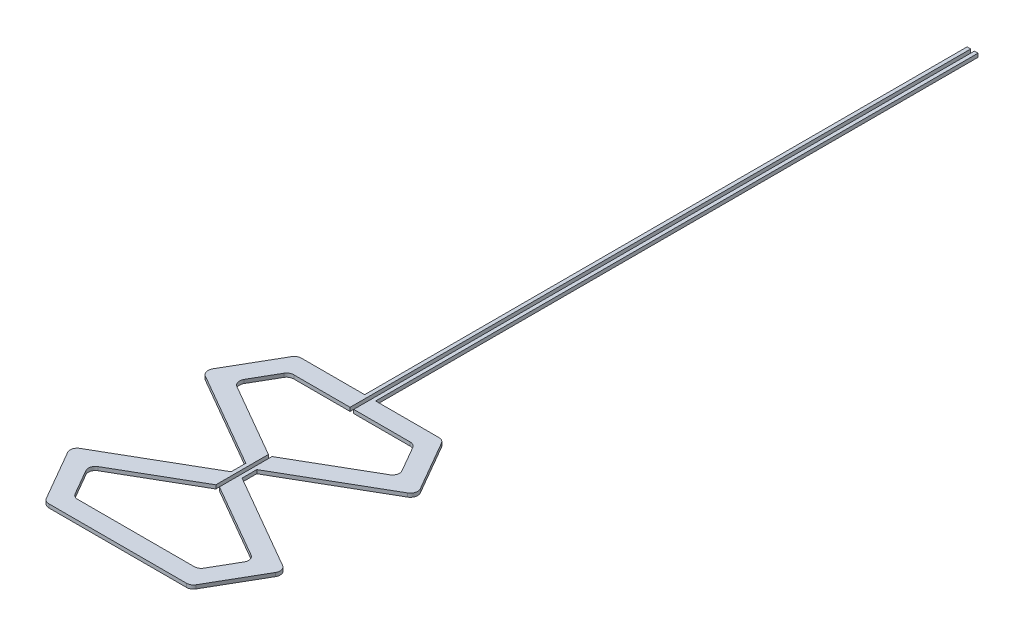
SolidWorks part; units mm, degrees
ref_plane "前视基准面" through (0, 0, 0) normal (0, 0, 1) x (1, 0, 0)
ref_plane "上视基准面" through (0, 0, 0) normal (0, 1, 0) x (1, 0, 0)
ref_plane "右视基准面" through (0, 0, 0) normal (1, 0, 0) x (0, 0, -1)
sketch "草图2" plane through (0, 0, 0) normal (0, 1, 0) x (1, 0, 0)
  line L0 (28.5, 19.9186) -> (20.5774, 33.641)
  line L1 (-28.551, -19.8303) -> (-20.5479, -33.692)
  line L2 (18.8453, 34.641) -> (-18.8453, 34.641)
  line L3 (-20.5774, 33.641) -> (-28.5, 19.9186)
  line L4 (15.9585, 29.641) -> (-15.9585, 29.641)
  line L5 (-18.9042, -34.641) -> (18.9042, -34.641)
  line L6 (20.5479, -33.692) -> (28.551, -19.8303)
  line L7 (-17.6906, 28.641) -> (-21.6699, 21.7487)
  line L8 (-27.7679, 17.1865) -> (0, 1.1547)
  line L9 (27.7679, 17.1865) -> (0, 1.1547)
  line L10 (-40, 0) -> (40, 0) construction
  line L11 (27.8562, -17.2375) -> (0, -1.1547)
  line L12 (-27.8562, -17.2375) -> (0, -1.1547)
  line L13 (-20.9378, 19.0167) -> (0, 6.9282)
  line L14 (21.0261, 19.0676) -> (0, 6.9282)
  line L15 (21.7208, 21.6604) -> (17.6906, 28.641)
  line L16 (-21.0261, -19.0676) -> (0, -6.9282)
  line L17 (30.5, 16.4545) -> (30, 17.3205) [skipped]
  line L18 (-30.5, -16.4545) -> (-30, -17.3205) [skipped]
  line L19 (21.0261, -19.0676) -> (0, -6.9282)
  line L20 (17.6612, -28.692) -> (21.7208, -21.6604)
  line L21 (-16.0174, -29.641) -> (16.0174, -29.641)
  line L22 (-21.7208, -21.6604) -> (-17.6612, -28.692)
  line L23 (-20, 34.641) -> (-29.5, 18.1865) construction
  line L24 (20, 34.641) -> (-20, 34.641) construction
  line L25 (-29.5, 18.1865) -> (0, 1.1547) construction
  line L26 (-17.1132, 29.641) -> (-22.6699, 20.0167) construction
  line L27 (-22.6699, 20.0167) -> (0, 6.9282) construction
  line L28 (17.1132, 29.641) -> (-17.1132, 29.641) construction
  line L29 (22.6699, 20.0167) -> (17.1132, 29.641) construction
  line L30 (29.5, 18.1865) -> (20, 34.641) construction
  line L31 (29.5, 18.1865) -> (0, 1.1547) construction
  line L32 (22.6699, 20.0167) -> (0, 6.9282) construction
  line L33 (-22.6699, -20.0167) -> (-17.1132, -29.641) construction
  line L34 (-22.6699, -20.0167) -> (0, -6.9282) construction
  line L35 (-29.5, -18.1865) -> (-20, -34.641) construction
  line L36 (-29.5, -18.1865) -> (0, -1.1547) construction
  line L37 (-17.1132, -29.641) -> (17.1132, -29.641) construction
  line L38 (-20, -34.641) -> (20, -34.641) construction
  line L39 (20, -34.641) -> (29.5, -18.1865) construction
  line L40 (17.1132, -29.641) -> (22.6699, -20.0167) construction
  line L41 (22.6699, -20.0167) -> (0, -6.9282) construction
  line L42 (29.5, -18.1865) -> (0, -1.1547) construction
  circle A0 centre (0, 0) radius 34.641 construction
  arc A1 (-20.5774, 33.641) -> (-18.8453, 34.641) centre (-18.8453, 32.641) cw
  arc A2 (-27.7679, 17.1865) -> (-28.5, 19.9186) centre (-26.7679, 18.9186) cw
  arc A3 (-21.6699, 21.7487) -> (-20.9378, 19.0167) centre (-19.9378, 20.7487) ccw
  arc A4 (-15.9585, 29.641) -> (-17.6906, 28.641) centre (-15.9585, 27.641) ccw
  arc A5 (17.6906, 28.641) -> (15.9585, 29.641) centre (15.9585, 27.641) ccw
  arc A6 (20.5774, 33.641) -> (18.8453, 34.641) centre (18.8453, 32.641) ccw
  arc A7 (27.7679, 17.1865) -> (28.5, 19.9186) centre (26.7679, 18.9186) ccw
  arc A8 (21.7208, 21.6604) -> (21.0261, 19.0676) centre (20.0771, 20.7114) cw
  arc A9 (-21.7208, -21.6604) -> (-21.0261, -19.0676) centre (-20.0771, -20.7114) cw
  arc A10 (-28.551, -19.8303) -> (-27.8562, -17.2375) centre (-26.9072, -18.8813) cw
  arc A11 (-17.6612, -28.692) -> (-16.0174, -29.641) centre (-16.0174, -27.743) ccw
  arc A12 (-20.5479, -33.692) -> (-18.9042, -34.641) centre (-18.9042, -32.743) ccw
  arc A13 (20.5479, -33.692) -> (18.9042, -34.641) centre (18.9042, -32.743) cw
  arc A14 (16.0174, -29.641) -> (17.6612, -28.692) centre (16.0174, -27.743) ccw
  arc A15 (21.0261, -19.0676) -> (21.7208, -21.6604) centre (20.0771, -20.7114) cw
  arc A16 (27.8562, -17.2375) -> (28.551, -19.8303) centre (26.9072, -18.8813) cw
  dimension "D4" = 2
  dimension "D5" = 2
  dimension "D6" = 2
  dimension "D7" = 2
  dimension "D8" = 2
  dimension "D9" = 2
  dimension "D1" = 2
  dimension "D10" = 1.8981
  dimension "D11" = 1.8981
  dimension "D12" = 1.8981
  dimension "D13" = 1.8981
  dimension "D14" = 1.8981
  dimension "D15" = 1.8981
  dimension "D16" = 1.8981
  dimension "D17" = 1.8981
  dimension "D18" = 1.8981
  dimension "D2" = 5
  dimension "D3" = 5
  dimension "D19" = 34.641
extrude "凸台-拉伸3" add sketch "草图2" along normal blind 1
sketch "草图3" plane through (0, 0, 0) normal (0, 1, 0) x (1, 0, 0)
  line L1 (0.5, 35.8677) -> (-0.5, 35.8677)
  line L2 (0.5, 35.8677) -> (0.5, -22.0113)
  line L3 (0.5, -22.0113) -> (-0.5, -22.0113)
  line L4 (-0.5, 35.8677) -> (-0.5, -22.0113)
  line L5 (0.5, 35.8677) -> (-0.5, -22.0113) construction
  line L6 (0.5, -22.0113) -> (-0.5, 35.8677) construction
  point P0 (0, 6.9282)
  dimension "D1" = 1
extrude "切除-拉伸3" cut sketch "草图3" against normal blind 2 and the other way blind 2
sketch "草图4" plane through (0, 0, 0) normal (0, 1, 0) x (1, 0, 0)
  line L0 (-1.5, 2.0207) -> (-1.5, -2.0207)
  line L1 (-27.7679, 17.1865) -> (-0.5, 1.4434) construction
  line L2 (-0.5, -1.4434) -> (-27.8562, -17.2375) construction
  line L3 (-0.5, 1.4434) -> (-0.5, -1.4434)
  line L4 (-1.5, 2.0207) -> (-0.5, 1.4434)
  line L5 (-0.5, -1.4434) -> (-1.5, -2.0207)
  line L6 (0.5, 1.4434) -> (0.5, -1.4434)
  line L7 (1.5, 2.0207) -> (1.5, -2.0207)
  line L8 (0.5, 1.4434) -> (27.7679, 17.1865) construction
  line L9 (27.8562, -17.2375) -> (0.5, -1.4434) construction
  line L10 (0.5, 1.4434) -> (1.5, 2.0207)
  line L11 (0.5, -1.4434) -> (1.5, -2.0207)
  line L12 (-0.5, 34.641) -> (-1.5, 34.641)
  line L13 (-0.5, 34.641) -> (-0.5, 200)
  line L14 (-1.5, 34.641) -> (-1.5, 200)
  line L15 (-0.5, 200) -> (-1.5, 200)
  line L16 (-0.5, 34.641) -> (-18.8453, 34.641) construction
  line L17 (0.5, 34.641) -> (1.5, 34.641)
  line L18 (0.5, 34.641) -> (0.5, 200)
  line L19 (1.5, 34.641) -> (1.5, 200)
  line L20 (0.5, 200) -> (1.5, 200)
  line L21 (18.8453, 34.641) -> (0.5, 34.641) construction
  dimension "D1" = 1
  dimension "D2" = 1
  dimension "D3" = 1
  dimension "D4" = 200
  dimension "D5" = 1
  dimension "D6" = 200
extrude "凸台-拉伸4" add sketch "草图4" along normal blind 1
